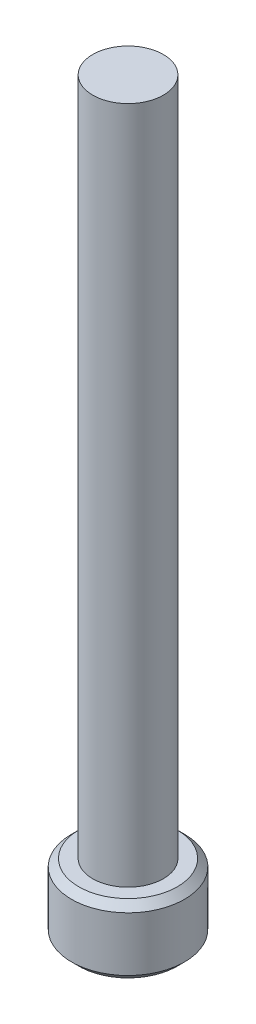
SolidWorks part; units mm, degrees
ref_plane "Front Plane" through (0, 0, 0) normal (0, 0, 1) x (1, 0, 0)
ref_plane "Top Plane" through (0, 0, 0) normal (0, 1, 0) x (1, 0, 0)
ref_plane "Right Plane" through (0, 0, 0) normal (1, 0, 0) x (0, 0, -1)
sketch "Sketch1" plane through (0, 0, 0) normal (0, 1, 0) x (1, 0, 0)
  circle A0 centre (0, 0) radius 2.4765
  dimension "D1" = 4.953
extrude "Boss-Extrude1" add sketch "Sketch1" along normal blind 47.625
sketch "Sketch2" plane through (0, 0, 0) normal (0, -1, 0) x (1, 0, 0)
  circle A0 centre (0, 0) radius 3.9624
  dimension "D1" = 7.9248
extrude "Boss-Extrude2" add sketch "Sketch2" along normal blind 4.826
sketch "Sketch3" plane through (0, -4.826, 0) normal (0, -1, 0) x (1, 0, 0)
  line L1 (2.2914, 0) -> (1.1457, 1.9844)
  line L2 (1.1457, 1.9844) -> (-1.1457, 1.9844)
  line L3 (-1.1457, 1.9844) -> (-2.2914, 0)
  line L4 (-2.2914, 0) -> (-1.1457, -1.9844)
  line L5 (-1.1457, -1.9844) -> (1.1457, -1.9844)
  line L6 (1.1457, -1.9844) -> (2.2914, 0)
  circle A0 centre (0, 0) radius 1.9844 construction
  dimension "D1" = 3.9688
extrude "Cut-Extrude1" cut sketch "Sketch3" against normal blind 2.286
chamfer "Chamfer1" distance 0.508 angle 45 2 edges at (0, -4.826, -3.9624) (0, 0, -3.9624)
